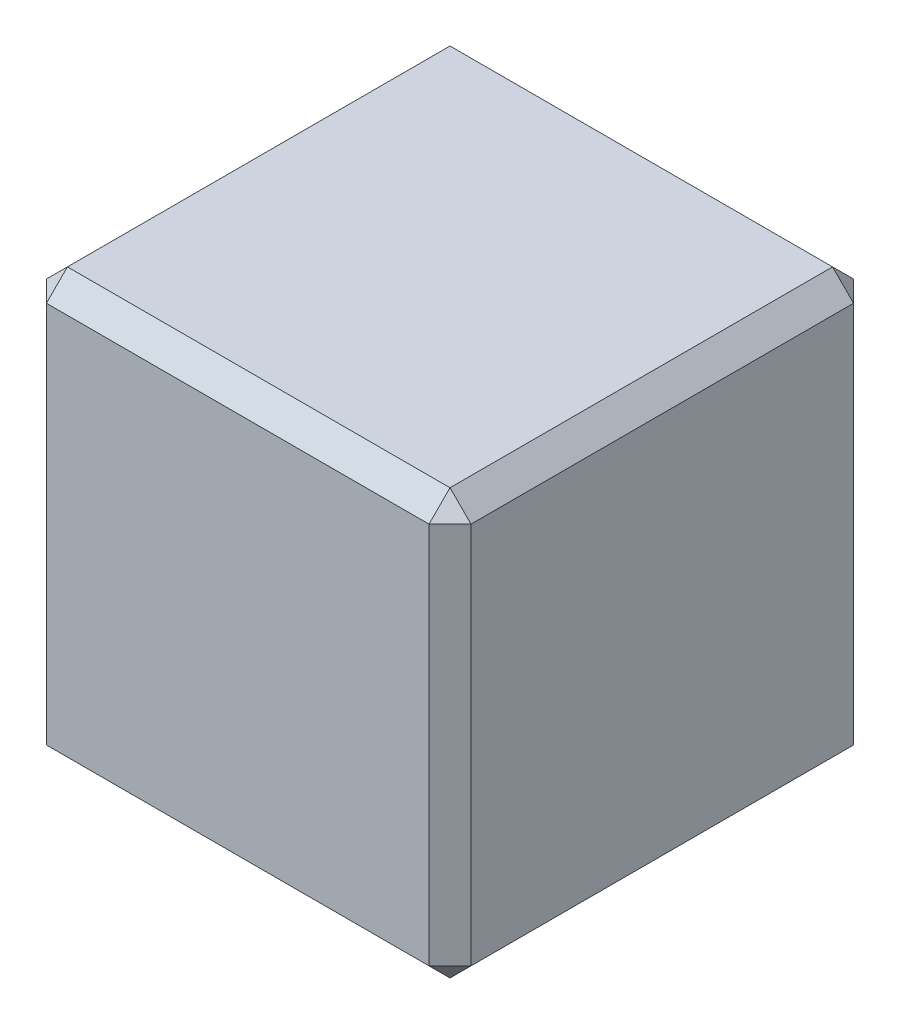
SolidWorks part; units mm, degrees
ref_plane "前视基准面" through (0, 0, 0) normal (0, 0, 1) x (1, 0, 0)
ref_plane "上视基准面" through (0, 0, 0) normal (0, 1, 0) x (1, 0, 0)
ref_plane "右视基准面" through (0, 0, 0) normal (1, 0, 0) x (0, 0, -1)
sketch "草图1" plane through (0, 0, 0) normal (0, 1, 0) x (1, 0, 0)
  line L1 (-50.54, 50.54) -> (50.54, 50.54)
  line L2 (-50.54, 50.54) -> (-50.54, -50.54)
  line L3 (-50.54, -50.54) -> (50.54, -50.54)
  line L4 (50.54, 50.54) -> (50.54, -50.54)
  line L5 (0, -50.54) -> (0, 50.54) construction
  line L6 (-50.54, 0) -> (50.54, 0) construction
  point P0 (0, 0)
  dimension "D1" = 101.08
extrude "凸台-拉伸1" add sketch "草图1" along normal blind 101.08
chamfer "倒角1" distance 5 angle 45 12 edges at (50.54, 0, 0) (50.54, 50.54, -50.54) (0, 0, -50.54) (0, 101.08, -50.54) (50.54, 101.08, 0) (0, 101.08, 50.54) (50.54, 50.54, 50.54) (0, 0, 50.54) (-50.54, 50.54, -50.54) (-50.54, 101.08, 0) (-50.54, 50.54, 50.54) (-50.54, 0, 0)
